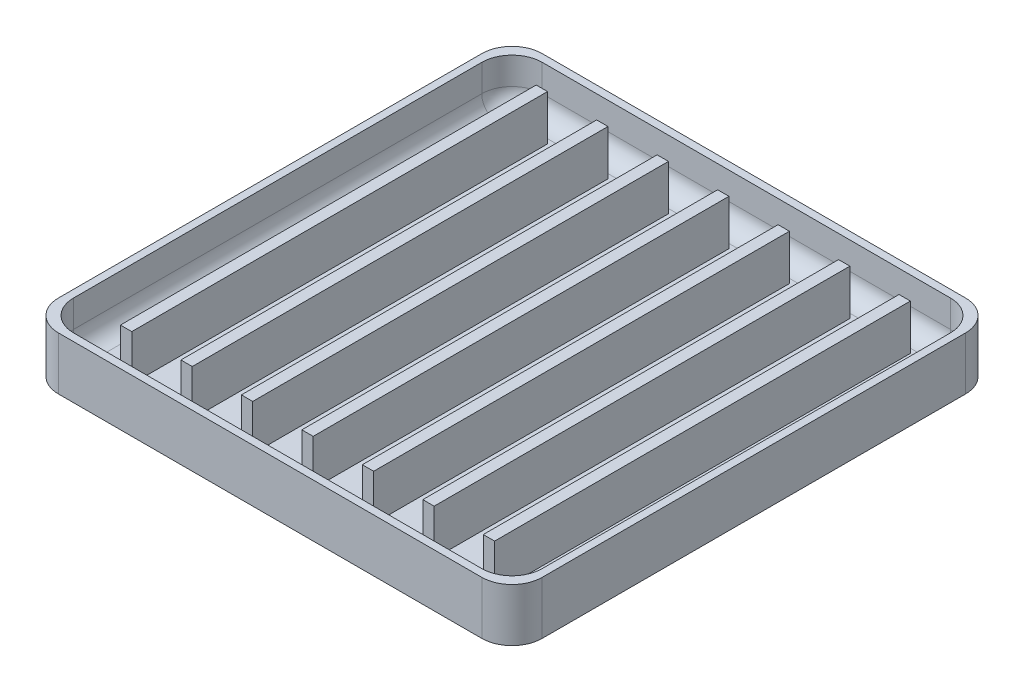
SolidWorks part; units mm, degrees
ref_plane "Front" through (0, 0, 0) normal (0, 0, 1) x (1, 0, 0)
ref_plane "Top" through (0, 0, 0) normal (0, 1, 0) x (1, 0, 0)
ref_plane "Right" through (0, 0, 0) normal (1, 0, 0) x (0, 0, -1)
sketch "Esquisse1" plane through (0, 0, 0) normal (0, 1, 0) x (1, 0, 0)
  line L1 (-50.8, 50.8) -> (50.8, 50.8)
  line L2 (-50.8, 50.8) -> (-50.8, -50.8)
  line L3 (-50.8, -50.8) -> (50.8, -50.8)
  line L4 (50.8, 50.8) -> (50.8, -50.8)
  line L5 (-50.8, 50.8) -> (50.8, -50.8) construction
  line L6 (-50.8, -50.8) -> (50.8, 50.8) construction
  point P0 (0, 0)
  dimension "D1" = 101.6
extrude "Boss.-Extru.1" add sketch "Esquisse1" along normal blind 11.1125
fillet "Congé1" radius 6.35 4 edges at (-50.8, 5.5562, -50.8) (50.8, 5.5562, -50.8) (-50.8, 5.5562, 50.8) (50.8, 5.5562, 50.8)
sketch "Esquisse2" plane through (0, 11.1125, 0) normal (0, 1, 0) x (1, 0, 0)
  line L1 (-42.8625, 49.2125) -> (42.8625, 49.2125)
  line L2 (-49.2125, 42.8625) -> (-49.2125, -42.8625)
  line L3 (-42.8625, -49.2125) -> (42.8625, -49.2125)
  line L4 (49.2125, 42.8625) -> (49.2125, -42.8625)
  line L5 (-49.2125, 49.2125) -> (49.2125, -49.2125) construction
  line L6 (-49.2125, -49.2125) -> (49.2125, 49.2125) construction
  arc A0 (-49.2125, -42.8625) -> (-42.8625, -49.2125) centre (-42.8625, -42.8625) ccw
  arc A1 (42.8625, -49.2125) -> (49.2125, -42.8625) centre (42.8625, -42.8625) ccw
  arc A2 (42.8625, 49.2125) -> (49.2125, 42.8625) centre (42.8625, 42.8625) cw
  arc A3 (-42.8625, 49.2125) -> (-49.2125, 42.8625) centre (-42.8625, 42.8625) ccw
  point P0 (0, 0)
  dimension "D2" = 6.35
  dimension "D1" = 98.425
extrude "Enlèv. mat.-Extru.1" cut sketch "Esquisse2" against normal blind 9.525
sketch "Esquisse3" plane through (0, 1.5875, 0) normal (0, 1, 0) x (1, 0, 0)
  line L0 (-44.45, -50.8) -> (44.45, -50.8) construction
  line L1 (-50, 0) -> (50, 0) construction
  line L2 (50.8, -44.45) -> (50.8, 44.45) construction
  line L3 (-50.8, 44.45) -> (-50.8, -44.45) construction
  line L5 (44.45, 50.8) -> (-44.45, 50.8) construction
  circle A0 centre (0, -23.876) radius 3.175
  circle A1 centre (0, 23.876) radius 3.175
  circle A2 centre (3.175, -9.525) radius 3.175
  circle A4 centre (-3.175, 9.525) radius 3.175
  circle A5 centre (-19.05, -1.5875) radius 3.175
  circle A6 centre (19.05, 2.54) radius 3.175
  dimension "D2" = 6.35
  dimension "D3" = 6.35
  dimension "D8" = 6.35
  dimension "D9" = 6.35
  dimension "D13" = 6.35
  dimension "D1" = 26.924
  dimension "D4" = 9.525
  dimension "D5" = 47.625
  dimension "D6" = 9.525
  dimension "D7" = 47.625
  dimension "D10" = 31.75
  dimension "D11" = 52.3875
  dimension "D12" = 31.75
  dimension "D14" = 48.26
extrude "Boss.-Extru.2" [suppressed] add sketch "Esquisse3" along normal blind 9.525
sketch "Esquisse4" plane through (0, 1.5875, 0) normal (0, 1, 0) x (1, 0, 0)
  line L0 (-42.8625, -49.2125) -> (42.8625, -49.2125) construction
  line L1 (-36.9888, 44.45) -> (-39.37, 44.45)
  line L2 (-36.9888, 44.45) -> (-36.9887, -42.8625)
  line L3 (-36.9887, -42.8625) -> (-39.37, -42.8625)
  line L4 (-39.37, 44.45) -> (-39.37, -42.8625)
  line L5 (-36.9888, 44.45) -> (-39.37, -42.8625) construction
  line L6 (-36.9887, -42.8625) -> (-39.37, 44.45) construction
  line L7 (44.45, 50.8) -> (-44.45, 50.8) construction
  line L8 (-50.8, 44.45) -> (-50.8, -44.45) construction
  point P0 (-38.1794, 0.7938)
  point P7 (-38.1794, 44.45)
  dimension "D1" = 2.3813
  dimension "D2" = 6.35
  dimension "D3" = 6.35
  dimension "D4" = 11.43
extrude "Boss.-Extru.3" add sketch "Esquisse4" along normal blind 9.525
pattern_linear "Répétition linéaire1" count 7 spacing 12.7 along (1, 0, 0) of "Boss.-Extru.3"
fillet "Congé2" radius 3.81 8 edges at (47.3526, 1.5875, -47.3526) (49.2125, 1.5875, 0) (47.3526, 1.5875, 47.3526) (0, 1.5875, 49.2125) (-47.3526, 1.5875, 47.3526) (-49.2125, 1.5875, 0) (-47.3526, 1.5875, -47.3526) (0, 1.5875, -49.2125)
